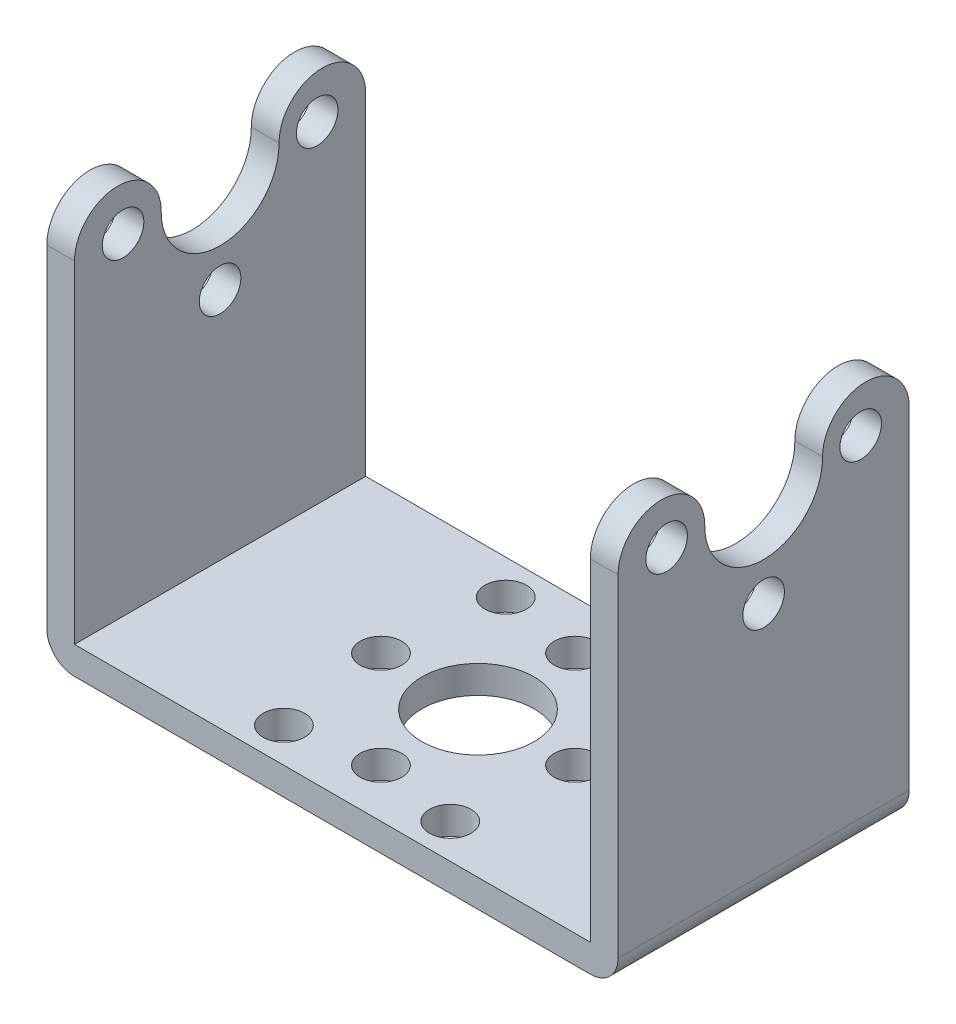
SolidWorks part; units mm, degrees
material "6061 Alloy"
ref_plane "Front Plane" through (0, 0, 0) normal (0, 0, 1) x (1, 0, 0)
ref_plane "Top Plane" through (0, 0, 0) normal (0, 1, 0) x (1, 0, 0)
ref_plane "Right Plane" through (0, 0, 0) normal (1, 0, 0) x (0, 0, -1)
sketch "Sketch1" plane through (0, 0, 0) normal (0, 1, 0) x (1, 0, 0)
  line L0 (-18.6, 10.5) -> (-18.6, -10.5) construction
  line L1 (-20.6, -10.5) -> (20.6, -10.5)
  line L2 (-20.6, -10.5) -> (-20.6, 10.5)
  line L3 (-20.6, 10.5) -> (20.6, 10.5)
  line L4 (20.6, -10.5) -> (20.6, 10.5)
  line L5 (18.6, 10.5) -> (18.6, -10.5) construction
  line L6 (-6, 10.5) -> (-6, -10.5) construction
  line L7 (0, 10.5) -> (0, -10.5) construction
  line L8 (6, 10.5) -> (6, -10.5) construction
  line L9 (-20.6, 8) -> (20.6, 8) construction
  line L10 (-20.6, 0) -> (20.6, 0) construction
  line L11 (-20.6, -8) -> (20.6, -8) construction
  circle A0 centre (0, 0) radius 7 construction
  circle A1 centre (0, 0) radius 4.05
  circle A2 centre (0, 7) radius 1.5
  circle A3 centre (7, 0) radius 1.5
  circle A4 centre (0, -7) radius 1.5
  circle A5 centre (-7, 0) radius 1.5
  circle A7 centre (6, -8) radius 1.5
  circle A8 centre (6, 8) radius 1.5
  circle A9 centre (-6, 8) radius 1.5
  circle A10 centre (-6, -8) radius 1.5
  point P4 (0, 10.5)
  point P6 (-20.6, 0)
  point P42 (0, 0)
  dimension "D5" = 14
  dimension "D6" = 8.1
  dimension "D7" = 3
  dimension "D8" = 3
  dimension "D9" = 3
  dimension "D10" = 3
  dimension "D15" = 3
  dimension "D16" = 3
  dimension "D17" = 3
  dimension "D18" = 3
  dimension "D1" = 41.2
  dimension "D2" = 2
  dimension "D3" = 2
  dimension "D4" = 21
  dimension "D11" = 6
  dimension "D12" = 6
  dimension "D13" = 8
  dimension "D14" = 8
extrude "Boss-Extrude1" add sketch "Sketch1" along normal blind 2
sketch "Sketch2" plane through (0, 2, 0) normal (0, 1, 0) x (1, 0, 0)
  line L0 (-20.6, -10.5) -> (20.6, -10.5) construction
  line L1 (-20.6, 10.5) -> (-18.6, 10.5)
  line L2 (-20.6, 10.5) -> (-20.6, -10.5)
  line L3 (-20.6, -10.5) -> (-18.6, -10.5)
  line L4 (-18.6, 10.5) -> (-18.6, -10.5)
  line L6 (20.6, 10.5) -> (18.6, 10.5)
  line L7 (20.6, 10.5) -> (20.6, -10.5)
  line L8 (20.6, -10.5) -> (18.6, -10.5)
  line L9 (18.6, 10.5) -> (18.6, -10.5)
  dimension "D1" = 2
  dimension "D2" = 2
extrude "Boss-Extrude2" add sketch "Sketch2" along normal blind 28.2
sketch "Sketch3" plane through (-20.6, 0, 0) normal (-1, 0, 0) x (0, 0, 1)
  line L0 (-10.5, 30.2) -> (18.4363, 30.2) construction
  line L1 (-10.5, 0) -> (18.4363, 0) construction
  line L2 (-10.5, 25.9) -> (10.5, 25.9) construction
  line L3 (-10.5, 30.2) -> (-10.5, 0) construction
  line L4 (10.5, 30.2) -> (10.5, 0) construction
  line L5 (-10.5, 25.9) -> (-4.25, 25.9) construction
  line L6 (-10.5, 2) -> (15.4935, 2) construction
  circle A0 centre (0, 25.9) radius 7 construction
  circle A1 centre (-7, 25.9) radius 1.5
  circle A2 centre (0, 18.9) radius 1.5
  circle A3 centre (7, 25.9) radius 1.5
  circle A4 centre (0, 25.9) radius 4.25
  dimension "D3" = 14
  dimension "D4" = 3
  dimension "D5" = 3
  dimension "D6" = 3
  dimension "D7" = 8.5
  dimension "D1" = 30.2
  dimension "D2" = 4.3
extrude "Cut-Extrude1" cut sketch "Sketch3" against normal through all
sketch "Sketch4" plane through (-20.6, 0, 0) normal (-1, 0, 0) x (0, 0, 1)
  line L0 (-8.4994, 25.9441) -> (10.6775, 25.9441) construction
  line L1 (-10.5, 30.2) -> (-10.5, 0) construction
  line L2 (10.5, 30.2) -> (10.5, 0) construction
  line L3 (-10.5, 25.9441) -> (-10.5, 30.2)
  line L4 (-10.5, 30.2) -> (10.5, 30.2)
  line L5 (10.5, 30.2) -> (10.5, 25.9441)
  circle A0 centre (-7, 25.9) radius 1.5 construction
  arc A1 (-10.5, 25.9441) -> (-4.2498, 25.9441) centre (-7.3749, 25.9441) cw
  circle A2 centre (0, 25.9) radius 4.25 construction
  arc A3 (10.5, 25.9441) -> (4.2498, 25.9441) centre (7.3749, 25.9441) ccw
  arc A5 (-4.2498, 25.9441) -> (4.2498, 25.9441) centre (0, 25.9441) ccw
extrude "Cut-Extrude2" cut sketch "Sketch4" against normal through all
fillet "Fillet1" radius 2 2 edges at (-20.6, 0, 0) (20.6, 0, 0)
